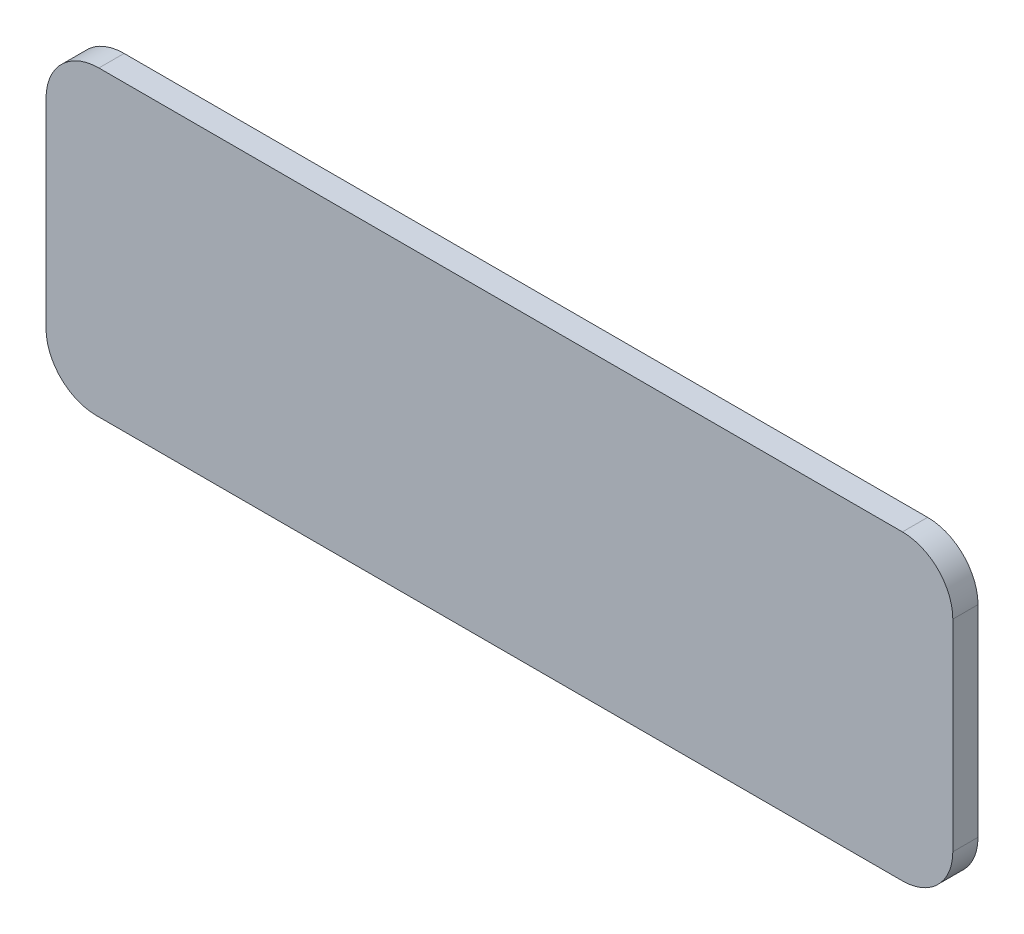
SolidWorks part; units mm, degrees
material "玻璃"
ref_plane "前视基准面" through (0, 0, 0) normal (0, 0, 1) x (1, 0, 0)
ref_plane "上视基准面" through (0, 0, 0) normal (0, 1, 0) x (1, 0, 0)
ref_plane "右视基准面" through (0, 0, 0) normal (1, 0, 0) x (0, 0, -1)
sketch "草图1" plane through (0, 0, 0) normal (0, 0, 1) x (1, 0, 0)
  line L1 (2, 0) -> (34, 0)
  line L2 (0, 2) -> (0, 9.9)
  line L3 (2.1, 12) -> (34, 12)
  line L4 (36, 2) -> (36, 10)
  arc A0 (0, 9.9) -> (2.1, 12) centre (2.1, 9.9) cw
  arc A1 (34, 12) -> (36, 10) centre (34, 10) cw
  arc A2 (36, 2) -> (34, 0) centre (34, 2) cw
  arc A3 (0, 2) -> (2, 0) centre (2, 2) ccw
  point P7 (0, 12)
  point P10 (36, 12)
  point P15 (0, 0)
  dimension "D3" = 2.1
  dimension "D4" = 2
  dimension "D1" = 12
  dimension "D2" = 36
extrude "凸台-拉伸1" add sketch "草图1" along normal blind 1
